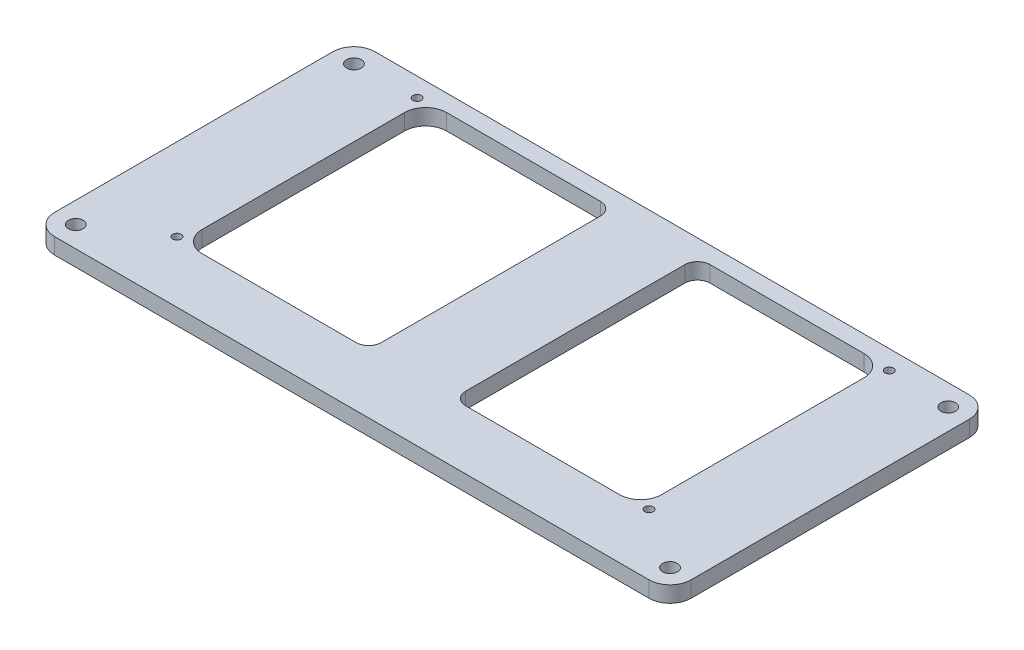
SolidWorks part; units mm, degrees
material "Maple"
ref_plane "Front Plane" through (0, 0, 0) normal (0, 0, 1) x (1, 0, 0)
ref_plane "Top Plane" through (0, 0, 0) normal (0, 1, 0) x (1, 0, 0)
ref_plane "Right Plane" through (0, 0, 0) normal (1, 0, 0) x (0, 0, -1)
sketch "Sketch1" plane through (0, 0, 0) normal (0, 1, 0) x (1, 0, 0)
  line L1 (0, 0) -> (121, 0)
  line L2 (0, 0) -> (0, -66)
  line L3 (0, -66) -> (121, -66)
  line L4 (121, 0) -> (121, -66)
  dimension "D1" = 121
  dimension "D2" = 66
extrude "Boss-Extrude1" add sketch "Sketch1" along normal blind 3.8
sketch "Sketch2" plane through (0, 3.8, 0) normal (0, 1, 0) x (1, 0, 0)
  line L0 (60.5, -66) -> (60.5, 0) construction
  line L2 (6, -4) -> (115, -4)
  line L3 (6, -4) -> (6, -62)
  line L4 (6, -62) -> (115, -62)
  line L5 (115, -4) -> (115, -62)
  line L6 (6, -4) -> (115, -62) construction
  line L7 (6, -62) -> (115, -4) construction
  line L9 (0, -66) -> (121, -66) construction
  line L10 (121, 0) -> (0, 0) construction
  line L11 (0, -33) -> (121, -33) construction
  line L12 (0, 0) -> (0, -66) construction
  line L13 (121, -66) -> (121, 0) construction
  point P4 (60.5, -33)
  dimension "D1" = 29
  dimension "D2" = 54.5
  dimension "D3" = 58
  dimension "D4" = 109
extrude "Cut-Extrude1" cut sketch "Sketch2" against normal through all
fillet "Fillet1" radius 5 4 edges at (6, 1.9, 62) (115, 1.9, 62) (115, 1.9, 4) (6, 1.9, 4)
sketch "Sketch3" plane through (0, 3.8, 0) normal (0, 1, 0) x (1, 0, 0)
  line L0 (60.5, 0) -> (60.5, -66) construction
  line L1 (121, 0) -> (0, 0) construction
  line L2 (0, -66) -> (121, -66) construction
  line L3 (11, -62) -> (110, -62) construction
  line L4 (50.5, -4) -> (70.5, -4)
  line L5 (50.5, -4) -> (50.5, -62)
  line L6 (50.5, -62) -> (70.5, -62)
  line L7 (70.5, -4) -> (70.5, -62)
  line L8 (50.5, -4) -> (70.5, -62) construction
  line L9 (50.5, -62) -> (70.5, -4) construction
  point P6 (60.5, -33)
  dimension "D1" = 20
extrude "Boss-Extrude2" add sketch "Sketch3" against normal through all
fillet "Fillet2" radius 3 4 edges at (70.5, 1.9, 62) (70.5, 1.9, 4) (50.5, 1.9, 62) (50.5, 1.9, 4)
sketch "Sketch4" plane through (0, 3.8, 0) normal (0, 1, 0) x (1, 0, 0)
  line L0 (60.5, -66) -> (60.5, 0) construction
  line L1 (121, -66) -> (121, 0) construction
  line L2 (0, -66) -> (121, -66) construction
  line L3 (121, 0) -> (0, 0) construction
  line L4 (0, 0) -> (0, -66) construction
  line L5 (0, -33) -> (121, -33) construction
  circle A0 centre (116.5, -61.5) radius 1
  circle A1 centre (116.5, -4.5) radius 1
  circle A2 centre (4.5, -4.5) radius 1
  circle A3 centre (4.5, -61.5) radius 1
  dimension "D1" = 2
  dimension "D6" = 2
  dimension "D7" = 2
  dimension "D10" = 2
  dimension "D3" = 28.5
  dimension "D2" = 56
  dimension "D5" = 28.5
  dimension "D4" = 56
  dimension "D11" = 28.5
  dimension "D8" = 28.5
  dimension "D9" = 56
  dimension "D12" = 56
extrude "Cut-Extrude2" cut sketch "Sketch4" against normal through all
sketch "Sketch5" plane through (0, 3.8, 0) normal (0, 1, 0) x (1, 0, 0)
  line L0 (121, 0) -> (0, 0) construction
  line L1 (-15, 0) -> (136, 0)
  line L2 (-15, 0) -> (-15, -76)
  line L3 (-15, -76) -> (136, -76)
  line L4 (136, 0) -> (136, -76)
  line L5 (0, 0) -> (0, -66) construction
  line L6 (121, -66) -> (121, 0) construction
  line L7 (0, -66) -> (121, -66) construction
  line L8 (0, 0) -> (0, -66)
  line L9 (0, -66) -> (121, -66)
  line L10 (121, -66) -> (121, 0)
  line M25 (0, 0) -> (0, -66)
  line M26 (0, -66) -> (121, -66)
  line M27 (121, -66) -> (121, 0)
  dimension "D1" = 15
  dimension "D2" = 15
  dimension "D3" = 10
extrude "Boss-Extrude3" add sketch "Sketch5" against normal through all contours L4 L1 L2 L3 M27 M26 M25
sketch "Sketch6" plane through (0, 0, 0) normal (0, -1, 0) x (-1, 0, 0)
  line L0 (15, 0) -> (15, -76) construction
  line L1 (15, -76) -> (-136, -76) construction
  line L2 (-136, 0) -> (-136, -76) construction
  line L3 (-136, 0) -> (15, 0) construction
  circle A0 centre (10, -71) radius 1.75
  circle A1 centre (10, -5) radius 1.75
  circle A2 centre (-131, -71) radius 1.75
  circle A3 centre (-131, -5) radius 1.75
  point P16 (0, 0)
  point P17 (0, 0)
  point P18 (0, 0)
  point P19 (0, 0)
  dimension "D1" = 3.5
  dimension "D2" = 5
  dimension "D3" = 5
  dimension "D4" = 5
  dimension "D5" = 5
extrude "Cut-Extrude3" cut sketch "Sketch6" against normal through all
fillet "Fillet3" radius 5 4 edges at (-15, 1.9, 0) (-15, 1.9, 76) (136, 1.9, 76) (136, 1.9, 0)
equation "\"D6@Sketch4\"=\"D1@Sketch4\""
equation "\"D7@Sketch4\"=\"D6@Sketch4\""
equation "\"D10@Sketch4\"=\"D7@Sketch4\""
equation "\"D5@Sketch4\"=\"D3@Sketch4\""
equation "\"D4@Sketch4\"=\"D2@Sketch4\""
equation "\"D11@Sketch4\"=\"D3@Sketch4\""
equation "\"D8@Sketch4\"=\"D11@Sketch4\""
equation "\"D9@Sketch4\"=\"D2@Sketch4\""
equation "\"D12@Sketch4\"=\"D9@Sketch4\""
equation "\"D3@Sketch6\"=\"D2@Sketch6\""
equation "\"D4@Sketch6\"=\"D2@Sketch6\""
equation "\"D5@Sketch6\"=\"D2@Sketch6\""
